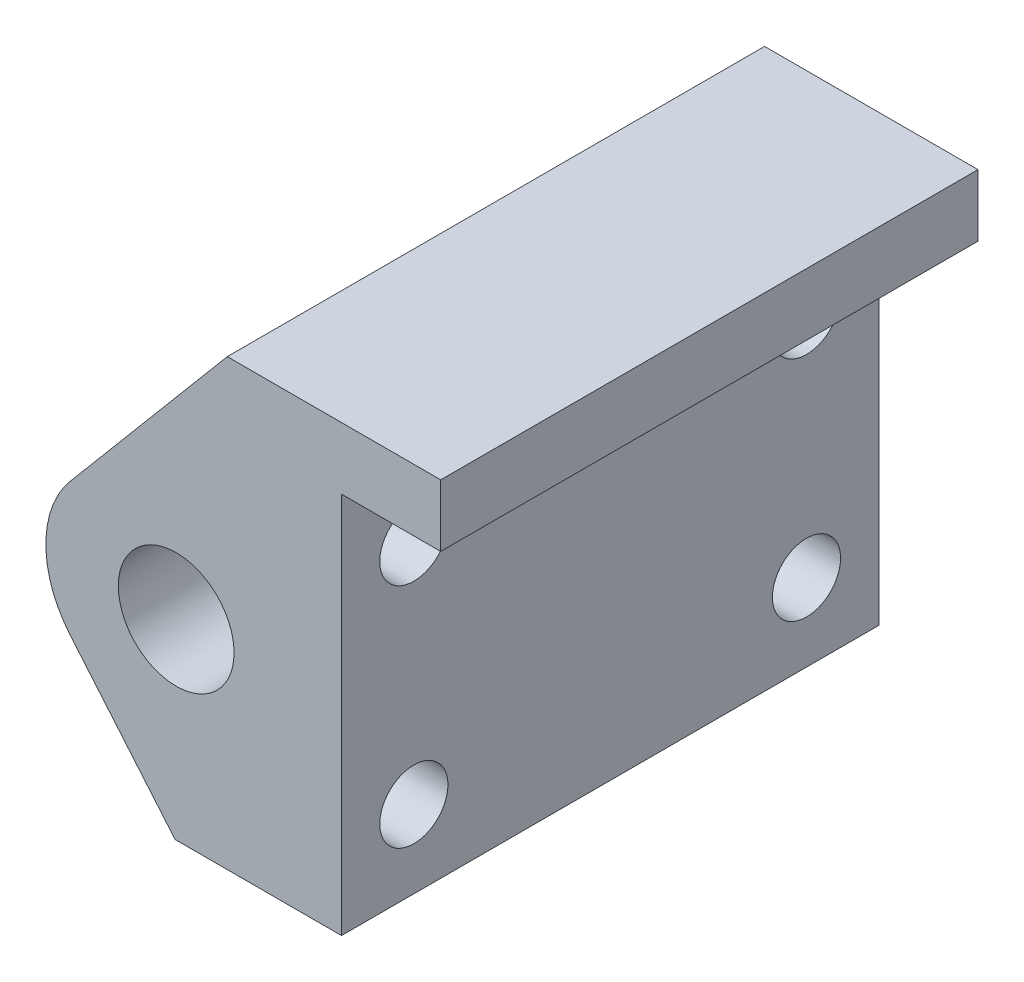
SolidWorks part; units mm, degrees
other "标注1"
sketch "草图6" plane through (7.8, 3, 26) normal (0.0743, -0.0151, 0.9971) x (0.9879, -0.135, -0.0757)
ref_plane "前视基准面" through (0, 0, 0) normal (0, 0, 1) x (1, 0, 0)
ref_plane "上视基准面" through (0, 0, 0) normal (0, 1, 0) x (1, 0, 0)
ref_plane "右视基准面" through (0, 0, 0) normal (1, 0, 0) x (0, 0, -1)
sketch "草图1" plane through (0, 0, 0) normal (0, 0, 1) x (1, 0, 0)
  line L0 (0, 0) -> (0, 30.5)
  line L2 (3, 6) -> (3, 24.5)
  line L3 (3, 24.5) -> (7.8, 24.5)
  line L6 (3, 15.25) -> (7.8, 15.25) construction
  line L7 (0, 30.5) -> (-10.1317, 18.4711)
  line L8 (-10.1317, 12.0289) -> (0, 0)
  line L9 (3, 6) -> (7.8, 6)
  line L10 (7.8, 0) -> (7.8, 6)
  line L12 (0, 30.5) -> (7.8, 30.5)
  line L17 (7.8, 30.5) -> (7.8, 24.5)
  line L18 (0, 0) -> (7.8, 0)
  circle A0 centre (-5, 15.25) radius 2.8
  circle A1 centre (-5, 15.25) radius 4.8
  arc A2 (-10.1317, 18.4711) -> (-10.1317, 12.0289) centre (-6.3075, 15.25) ccw
  dimension "D1" = 4.8
  dimension "D7" = 6
  dimension "D2" = 5.6
  dimension "D4" = 2
  dimension "D9" = 6
  dimension "D10" = 5
  dimension "D3" = 18.5
  dimension "D5" = 5
  dimension "D6" = 3
  dimension "D8" = 6
extrude "凸台-拉伸1" add sketch "草图1" along normal blind 26
sketch "草图2" plane through (3, 0, 0) normal (1, 0, 0) x (0, 0, -1)
  line L0 (0, 6) -> (0, 24.5) construction
  line L1 (-26, 6.25) -> (0, 6.25)
  line L2 (-26, 6.25) -> (-26, 24.25)
  line L3 (-26, 24.25) -> (0, 24.25)
  line L4 (0, 6.25) -> (0, 24.25)
  line L5 (-13, 24.25) -> (-13, 6.25) construction
  line L6 (-26, 15.25) -> (0, 15.25) construction
  line L7 (-26, 24.5) -> (0, 24.5) construction
  line L8 (-26, 6) -> (0, 6) construction
  line L9 (-26, 6) -> (-26, 24.5) construction
  circle A0 centre (-22.5, 20.75) radius 1.65
  circle A1 centre (-22.5, 9.75) radius 1.65
  circle A3 centre (-3.5, 9.75) radius 1.65
  circle A4 centre (-3.5, 20.75) radius 1.65
  point P14 (-3.5, 9.75)
  dimension "D3" = 3.3
  dimension "D1" = 18
  dimension "D2" = 26
  dimension "D4" = 19
  dimension "D5" = 11
extrude "切除-拉伸2" cut sketch "草图2" against normal through all contours A4 | A1 | A0 | A3
sketch "草图4" plane through (7.8, 0, 0) normal (1, 0, 0) x (0, 0, -1)
  line L0 (-26, 30.5) -> (0, 30.5) construction
  line L1 (-26, 30.5) -> (0, 30.5)
  line L2 (-26, 30.5) -> (-26, 27.5)
  line L3 (-26, 27.5) -> (0, 27.5)
  line L4 (0, 30.5) -> (0, 27.5)
  line L5 (-13, 24.5) -> (-13, 30.5) construction
  line L6 (-26, 24.5) -> (0, 24.5) construction
  line L7 (-26, 24.5) -> (0, 24.5) construction
  line L8 (-26, 15.25) -> (4.0257, 15.25) construction
  line L9 (-26, 6) -> (-26, 24.5) construction
  line L10 (0, 0) -> (0, 3)
  line L11 (-26, 3) -> (0, 3)
  line L12 (-26, 0) -> (-26, 3)
  line L13 (-26, 0) -> (0, 0)
  line L14 (0, 30.5) -> (0, 24.5) construction
  dimension "D1" = 3
  dimension "D2" = 3
extrude "下部切削" cut sketch "草图4" against normal up to next
sketch "草图7" plane through (7.8, 0, 0) normal (1, 0, 0) x (0, 0, -1)
  line L0 (0, 3) -> (0, 6) construction
  line L1 (-26, 3) -> (0, 3)
  line L2 (-26, 3) -> (-26, 6)
  line L3 (-26, 6) -> (0, 6)
  line L4 (0, 3) -> (0, 6)
  line L5 (-26, 6) -> (0, 6) construction
  dimension "D1" = 3
extrude "切除-拉伸3" cut sketch "草图7" against normal up to next
